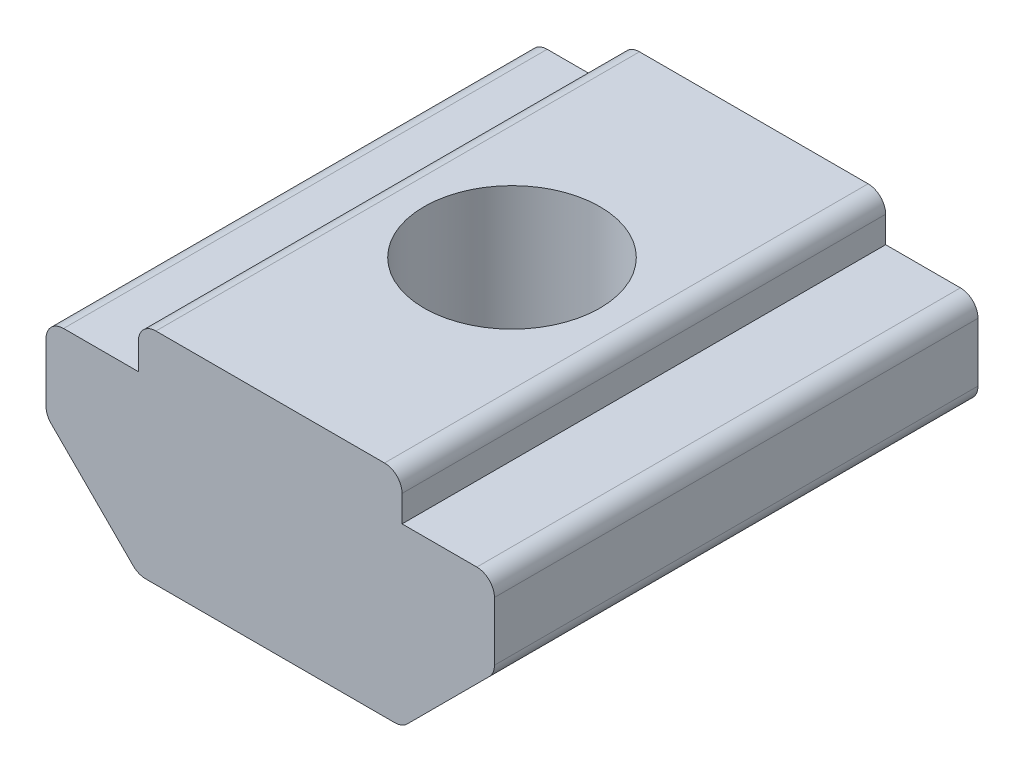
SolidWorks part; units mm, degrees
ref_plane "前视基准面" through (0, 0, 0) normal (0, 0, 1) x (1, 0, 0)
ref_plane "上视基准面" through (0, 0, 0) normal (0, 1, 0) x (1, 0, 0)
ref_plane "右视基准面" through (0, 0, 0) normal (1, 0, 0) x (0, 0, -1)
sketch "草图1" plane through (0, 0, 0) normal (0, 0, 1) x (1, 0, 0)
  line L0 (-5.1, 0) -> (-3, 0)
  line L1 (-3, 0) -> (-3, 1)
  line L2 (-3, 1) -> (3, 1)
  line L3 (3, 1) -> (3, 0)
  line L4 (3, 0) -> (5.1, 0)
  line L5 (5.1, 0) -> (5.1, -1.9)
  line L6 (5.1, -1.9) -> (3, -4)
  line L7 (3, -4) -> (-3, -4)
  line L8 (-3, -4) -> (-5.1, -1.9)
  line L9 (-5.1, -1.9) -> (-5.1, 0)
  point P12 (0, 1)
  dimension "D1" = 5
  dimension "D2" = 4
  dimension "D3" = 10.2
  dimension "D4" = 6
  dimension "D5" = 6
extrude "凸台-拉伸1" add sketch "草图1" along normal mid plane 11
sketch "草图2" plane through (0, 1, 0) normal (0, 1, 0) x (1, 0, 0)
  circle A0 centre (0, 0) radius 2
  dimension "D1" = 4
extrude "切除-拉伸1" cut sketch "草图2" against normal through all
fillet "圆角1" radius 0.4 8 edges at (3, 1, 0) (-3, 1, 0) (-5.1, 0, 0) (-5.1, -1.9, 0) (-3, -4, 0) (3, -4, 0) (5.1, -1.9, 0) (5.1, 0, 0)
